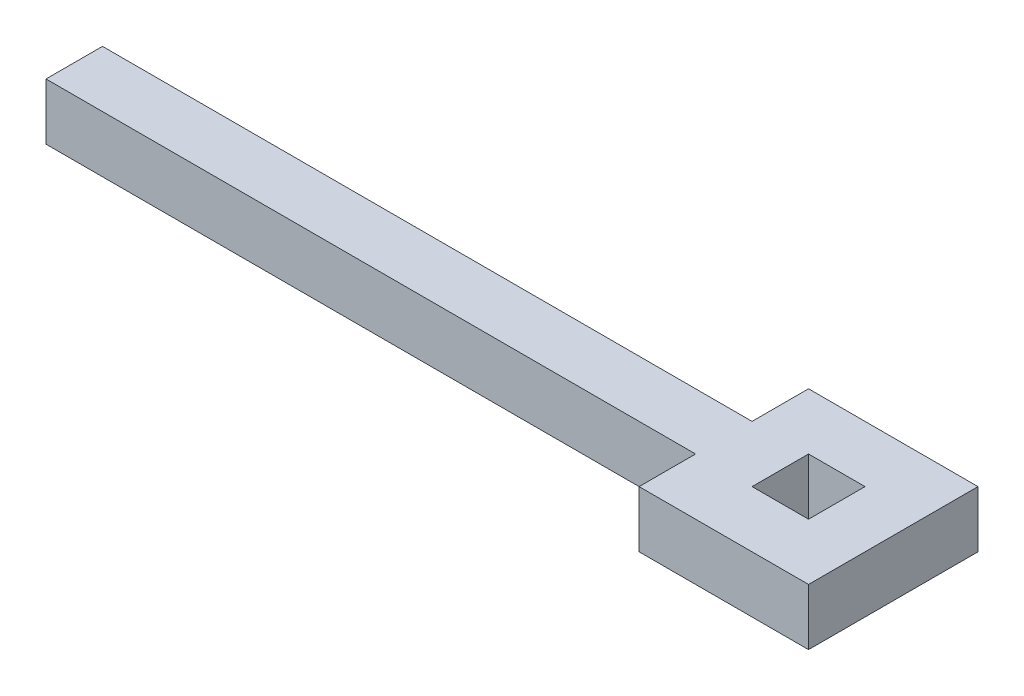
SolidWorks part; units mm, degrees
ref_plane "Front" through (0, 0, 0) normal (0, 0, 1) x (1, 0, 0)
ref_plane "Top" through (0, 0, 0) normal (0, 1, 0) x (1, 0, 0)
ref_plane "Right" through (0, 0, 0) normal (1, 0, 0) x (0, 0, -1)
sketch "Sketch2" plane through (0, 0, 0) normal (0, 1, 0) x (1, 0, 0)
  line L1 (0, 0) -> (-146.05, 0)
  line L2 (0, 0) -> (0, 12.7)
  line L3 (0, 12.7) -> (-146.05, 12.7)
  line L4 (-146.05, 0) -> (-146.05, 12.7)
  dimension "D1" = 146.05
  dimension "D2" = 12.7
extrude "Boss-Extrude1" add sketch "Sketch2" along normal blind 12.7
sketch "Sketch3" plane through (0, 0, 0) normal (1, 0, 0) x (0, 0, -1)
  line L0 (0, 12.7) -> (12.7, 12.7) construction
  line L1 (-12.7, 0) -> (25.4, 0)
  line L2 (-12.7, 0) -> (-12.7, 12.7)
  line L3 (-12.7, 12.7) -> (25.4, 12.7)
  line L4 (25.4, 0) -> (25.4, 12.7)
  line L5 (0, 0) -> (12.7, 0) construction
  line L6 (-12.7, 6.35) -> (0, 6.35) construction
  line L7 (0, 12.7) -> (0, 0) construction
  line L8 (12.7, 6.35) -> (25.4, 6.35) construction
  line L9 (12.7, 12.7) -> (12.7, 0) construction
  dimension "D1" = 38.1
extrude "Boss-Extrude2" add sketch "Sketch3" along normal blind 38.1
sketch "Sketch4" plane through (0, 12.7, 0) normal (0, 1, 0) x (1, 0, 0)
  line L0 (0, 25.4) -> (12.7, 12.7) construction
  line L1 (12.7, 0) -> (25.4, 0)
  line L2 (12.7, 0) -> (12.7, 12.7)
  line L3 (12.7, 12.7) -> (25.4, 12.7)
  line L4 (25.4, 0) -> (25.4, 12.7)
  line L5 (25.4, 12.7) -> (38.1, 25.4) construction
  line L6 (0, -12.7) -> (12.7, 0) construction
  line L7 (25.4, 0) -> (38.1, -12.7) construction
  dimension "D1" = 12.7
extrude "Cut-Extrude1" cut sketch "Sketch4" against normal blind 38.1
